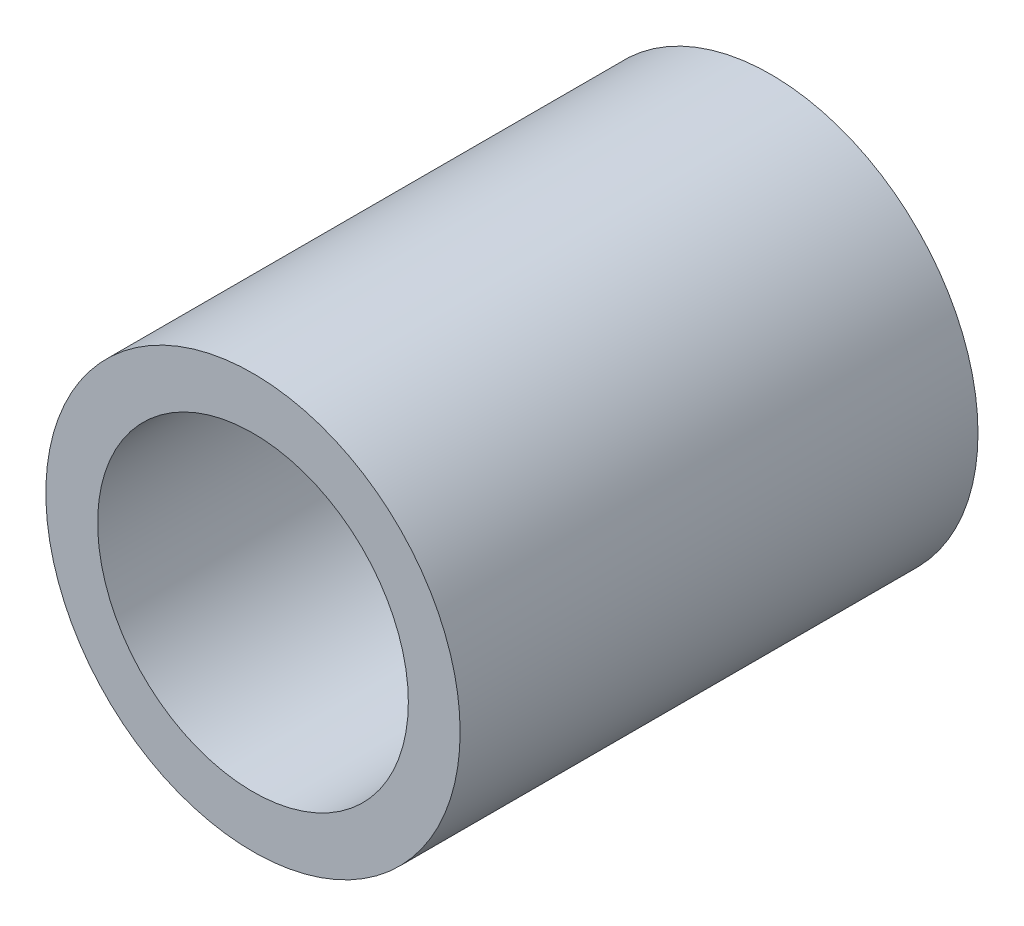
SolidWorks part; units mm, degrees
ref_plane "Płaszczyzna przednia" through (0, 0, 0) normal (0, 0, 1) x (1, 0, 0)
ref_plane "Płaszczyzna górna" through (0, 0, 0) normal (0, 1, 0) x (1, 0, 0)
ref_plane "Płaszczyzna prawa" through (0, 0, 0) normal (1, 0, 0) x (0, 0, -1)
sketch "Sketch1" plane through (0, 0, 0) normal (0, 0, 1) x (1, 0, 0)
  circle A0 centre (0, 0) radius 6
  circle A1 centre (0, 0) radius 8
  dimension "D1" = 12
  dimension "D2" = 2
extrude "Boss-Extrude1" add sketch "Sketch1" along normal blind 20
